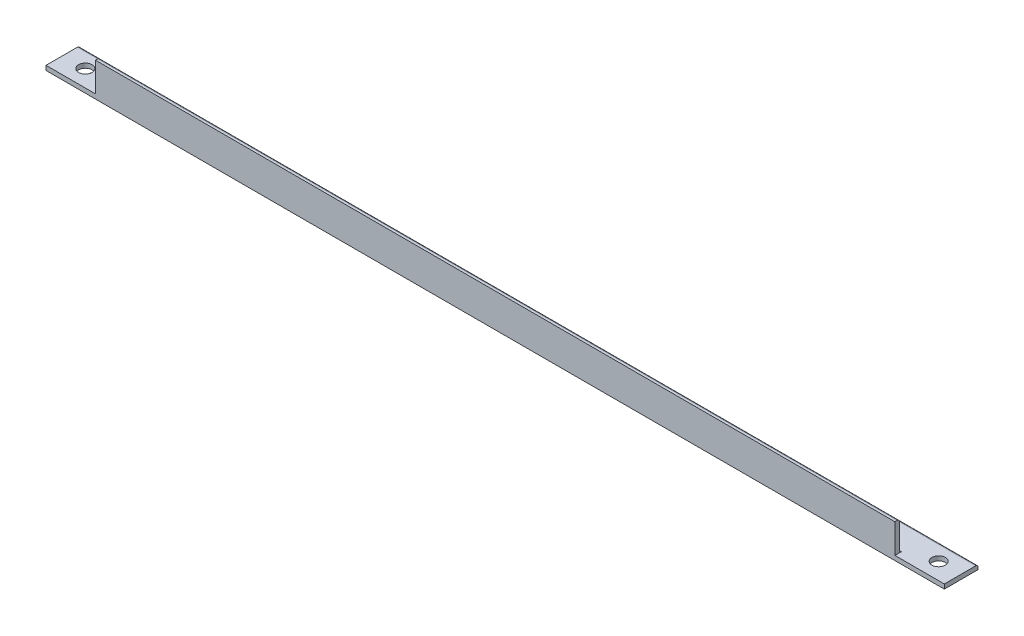
SolidWorks part; units mm, degrees
material "Простая углеродистая сталь"
ref_plane "Front" through (0, 0, 0) normal (0, 0, 1) x (1, 0, 0)
ref_plane "Top" through (0, 0, 0) normal (0, 1, 0) x (1, 0, 0)
ref_plane "Right" through (0, 0, 0) normal (1, 0, 0) x (0, 0, -1)
sketch "Эскиз1" plane through (0, 0, 0) normal (1, 0, 0) x (0, 0, -1)
  line L0 (0, 0) -> (0, 15)
  line L1 (0, 0) -> (15, 0)
  line L2 (15, 0) -> (15, 1)
  line L3 (14, 2) -> (3, 2)
  line L4 (2, 3) -> (2, 14)
  line L5 (1, 15) -> (0, 15)
  arc A0 (15, 1) -> (14, 2) centre (14, 1) ccw
  arc A1 (3, 2) -> (2, 3) centre (3, 3) cw
  arc A2 (2, 14) -> (1, 15) centre (1, 14) ccw
  point P9 (15, 2)
  point P14 (2, 15)
  dimension "D5" = 1
  dimension "D1" = 15
  dimension "D2" = 15
  dimension "D3" = 2
  dimension "D4" = 2
extrude "Бобышка-Вытянуть1" add sketch "Эскиз1" along normal blind 400
sketch "Эскиз2" plane through (0, 0, 0) normal (0, 0, 1) x (1, 0, 0)
  line L0 (400, 15) -> (0, 15) construction
  line L1 (400, 15) -> (378, 15)
  line L2 (400, 15) -> (400, 2)
  line L3 (400, 2) -> (378, 2)
  line L4 (378, 15) -> (378, 2)
  line L5 (400, 15) -> (400, 0) construction
  line L7 (0, 15) -> (22, 15)
  line L8 (0, 15) -> (0, 2)
  line L9 (0, 2) -> (22, 2)
  line L10 (22, 15) -> (22, 2)
  dimension "D1" = 13
  dimension "D2" = 22
  dimension "D3" = 13
  dimension "D4" = 22
extrude "Вырез-Вытянуть1" cut sketch "Эскиз2" against normal through all
sketch "Эскиз3" plane through (0, 2, 0) normal (0, 1, 0) x (1, 0, 0)
  line L0 (400, 14) -> (400, 0) construction
  line L1 (400, 15) -> (0, 15) construction
  line L2 (0, 14) -> (0, 0) construction
  circle A0 centre (390, 7.5) radius 3
  circle A1 centre (10, 7.5) radius 3
  dimension "D1" = 6
  dimension "D2" = 10
  dimension "D3" = 7.5
  dimension "D4" = 6
  dimension "D5" = 7.5
  dimension "D6" = 10
extrude "Вырез-Вытянуть2" cut sketch "Эскиз3" against normal through all
